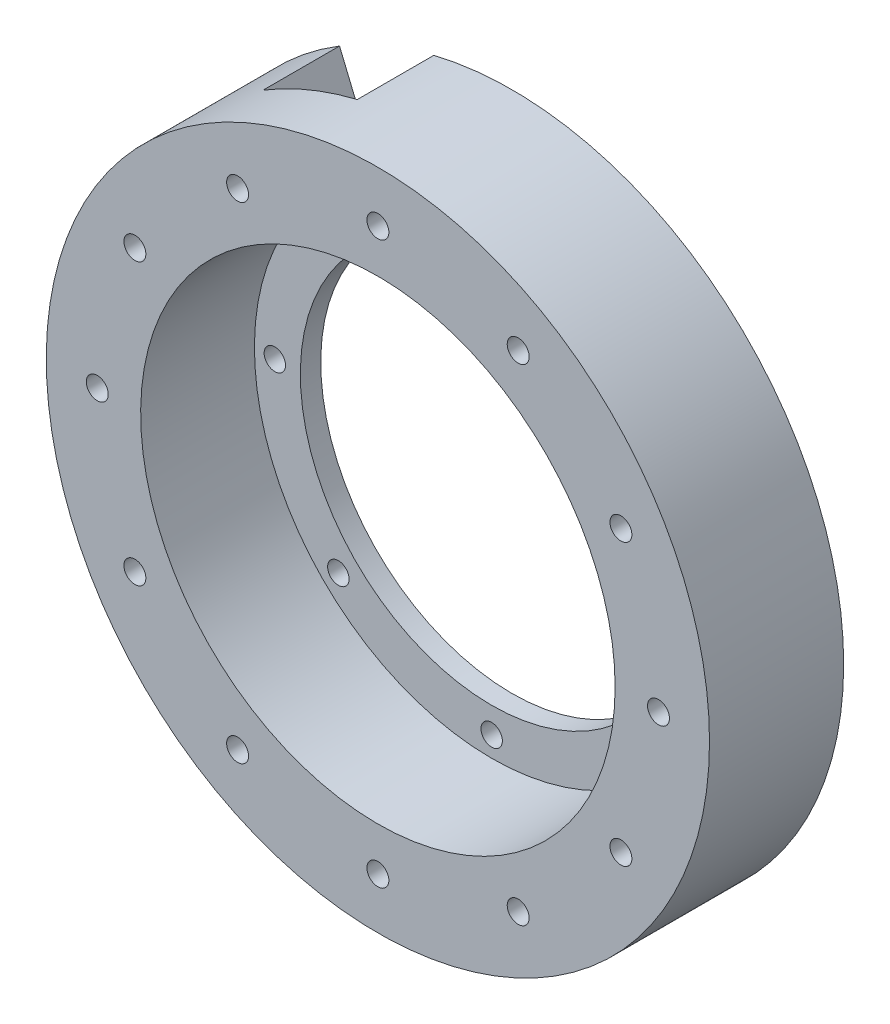
SolidWorks part; units mm, degrees
material "ABS"
ref_plane "前视基准面" through (0, 0, 0) normal (0, 0, 1) x (1, 0, 0)
ref_plane "上视基准面" through (0, 0, 0) normal (0, 1, 0) x (1, 0, 0)
ref_plane "右视基准面" through (0, 0, 0) normal (1, 0, 0) x (0, 0, -1)
other "Configuration Table"
sketch "草图1" plane through (0, 0, 0) normal (0, 0, 1) x (1, 0, 0)
  circle A1 centre (0, 0) radius 65
  dimension "D1" = 130
extrude "凸台-拉伸1" add sketch "草图1" along normal blind 5
sketch "草图2" plane through (0, 0, 5) normal (0, 0, 1) x (1, 0, 0)
  circle A0 centre (0, 0) radius 46.5
  circle A1 centre (0, 0) radius 65 construction
  circle A2 centre (0, 0) radius 65
  dimension "D1" = 93
extrude "凸台-拉伸2" add sketch "草图2" along normal blind 21.3
sketch "草图3" plane through (0, 0, 5) normal (0, 0, 1) x (1, 0, 0)
  circle A0 centre (0, 0) radius 42.5 construction
  circle A1 centre (0, 42.5) radius 2.1
  circle A2 centre (30.052, 30.052) radius 2.1
  circle A3 centre (42.5, 0) radius 2.1
  circle A4 centre (30.052, -30.052) radius 2.1
  circle A5 centre (0, -42.5) radius 2.1
  circle A6 centre (-30.052, -30.052) radius 2.1
  circle A7 centre (-42.5, 0) radius 2.1
  circle A8 centre (-30.052, 30.052) radius 2.1
  point P21 (0, 0)
  dimension "D1" = 85
  dimension "D2" = 4.2
  dimension "D3" = 8
extrude "切除-拉伸1" cut sketch "草图3" against normal blind 21.3
sketch "草图4" plane through (0, 0, 0) normal (0, 0, -1) x (-1, 0, 0)
  circle A0 centre (0, 0) radius 37.5
  dimension "D1" = 75
extrude "切除-拉伸2" cut sketch "草图4" against normal blind 21.3
sketch "草图5" plane through (0, 0, 0) normal (0, 0, -1) x (-1, 0, 0)
  line L0 (0, 42.5) -> (0, 0) construction
  line L1 (0, 0) -> (30.052, 30.052) construction
  line L2 (0, 0) -> (26.7877, 64.6713) construction
  line L3 (34.4496, 57.0373) -> (19.2362, 20.309)
  line L4 (34.4496, 57.0373) -> (15.972, 64.691)
  line L5 (19.2362, 20.309) -> (0.7586, 27.9627)
  line L6 (15.972, 64.691) -> (0.7586, 27.9627)
  line L7 (34.4496, 57.0373) -> (0.7586, 27.9627) construction
  line L8 (19.2362, 20.309) -> (15.972, 64.691) construction
  point P8 (17.6041, 42.5)
  dimension "D1" = 22.5
  dimension "D2" = 20
extrude "切除-拉伸3" cut sketch "草图5" against normal blind 15
sketch "草图6" plane through (0, 0, 5) normal (0, 0, 1) x (1, 0, 0)
  circle A0 centre (0, 0) radius 55 construction
  circle A1 centre (0, 55) radius 2.15
  circle A2 centre (27.5, 47.6314) radius 2.15
  circle A3 centre (47.6314, 27.5) radius 2.15
  circle A4 centre (55, 0) radius 2.15
  circle A5 centre (47.6314, -27.5) radius 2.15
  circle A6 centre (27.5, -47.6314) radius 2.15
  circle A7 centre (0, -55) radius 2.15
  circle A8 centre (-27.5, -47.6314) radius 2.15
  circle A9 centre (-47.6314, -27.5) radius 2.15
  circle A10 centre (-55, 0) radius 2.15
  circle A11 centre (-47.6314, 27.5) radius 2.15
  circle A12 centre (-27.5, 47.6314) radius 2.15
  point P0 (0, 42.5)
  point P32 (0, 0)
  dimension "D1" = 110
  dimension "D2" = 4.3
  dimension "D3" = 12
extrude "切除-拉伸4" cut sketch "草图6" along normal through all and the other way through all
sketch "草图7" plane through (0, 0, 5) normal (0, 0, 1) x (1, 0, 0)
  line L2 (-23.0698, 29.5641) -> (-26.6172, 38.1284)
  line L3 (-8.1396, 45.7821) -> (-4.5922, 37.2178)
  line L4 (-23.0698, 29.5641) -> (-26.6172, 38.1284)
  line L5 (-8.1396, 45.7821) -> (-4.5922, 37.2178)
  arc A2 (-26.6172, 38.1284) -> (-8.1396, 45.7821) centre (0, 0) ccw
  arc A3 (-23.0698, 29.5641) -> (-4.5922, 37.2178) centre (0, 0) ccw
  arc A4 (-26.6172, 38.1284) -> (-8.1396, 45.7821) centre (0, 0) ccw
  arc A5 (-23.0698, 29.5641) -> (-4.5922, 37.2178) centre (0, 0) ccw
  dimension "D1" = 0
extrude "切除-拉伸5" cut sketch "草图7" against normal blind 1
